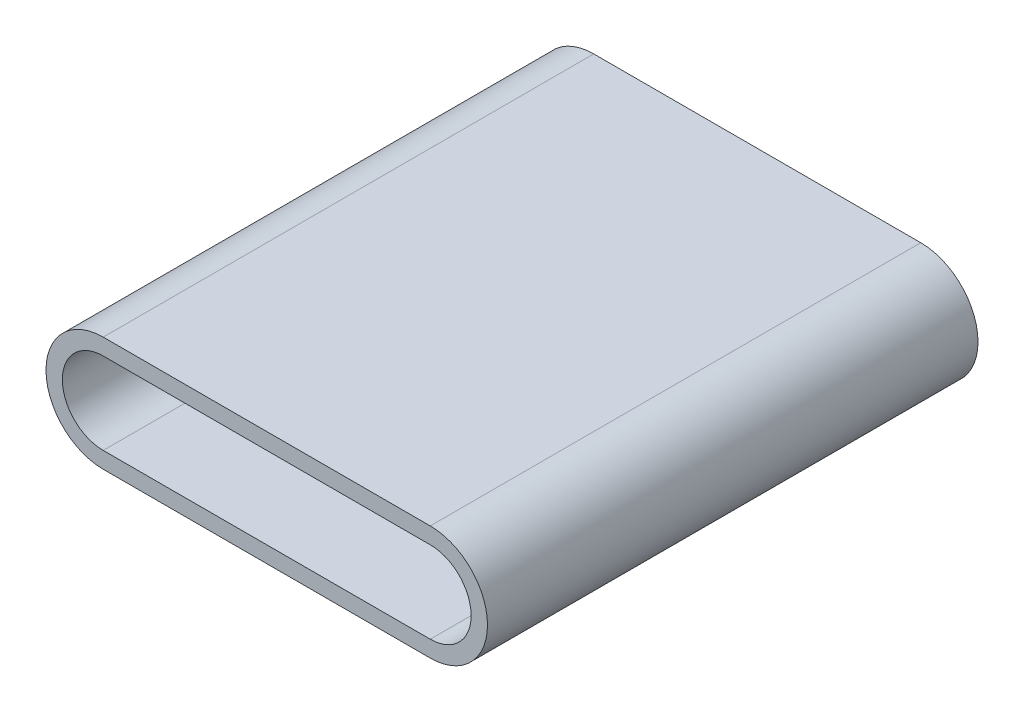
SolidWorks part; units mm, degrees
ref_plane "Front Plane" through (0, 0, 0) normal (0, 0, 1) x (1, 0, 0)
ref_plane "Top Plane" through (0, 0, 0) normal (0, 1, 0) x (1, 0, 0)
ref_plane "Right Plane" through (0, 0, 0) normal (1, 0, 0) x (0, 0, -1)
sketch "Sketch2" plane through (0, 0, 0) normal (0, 0, 1) x (1, 0, 0)
  line L5 (-10, 3.5) -> (10, 3.5)
  line L6 (10, -3.5) -> (-10, -3.5)
  line L10 (-10, 2.5) -> (10, 2.5)
  line L11 (10, -2.5) -> (-10, -2.5)
  arc A0 (10, 3.5) -> (10, -3.5) centre (10, 0) cw
  arc A1 (-10, -3.5) -> (-10, 3.5) centre (-10, 0) cw
  arc A2 (10, 2.5) -> (10, -2.5) centre (10, 0) cw
  arc A3 (-10, -2.5) -> (-10, 2.5) centre (-10, 0) cw
  point P7 (0, 3.5)
  point P8 (0, -3.5)
  point P16 (0, 0)
  dimension "D2" = 3.5
  dimension "D1" = 20
  dimension "D3" = 1
extrude "Boss-Extrude1" add sketch "Sketch2" along normal mid plane 30
